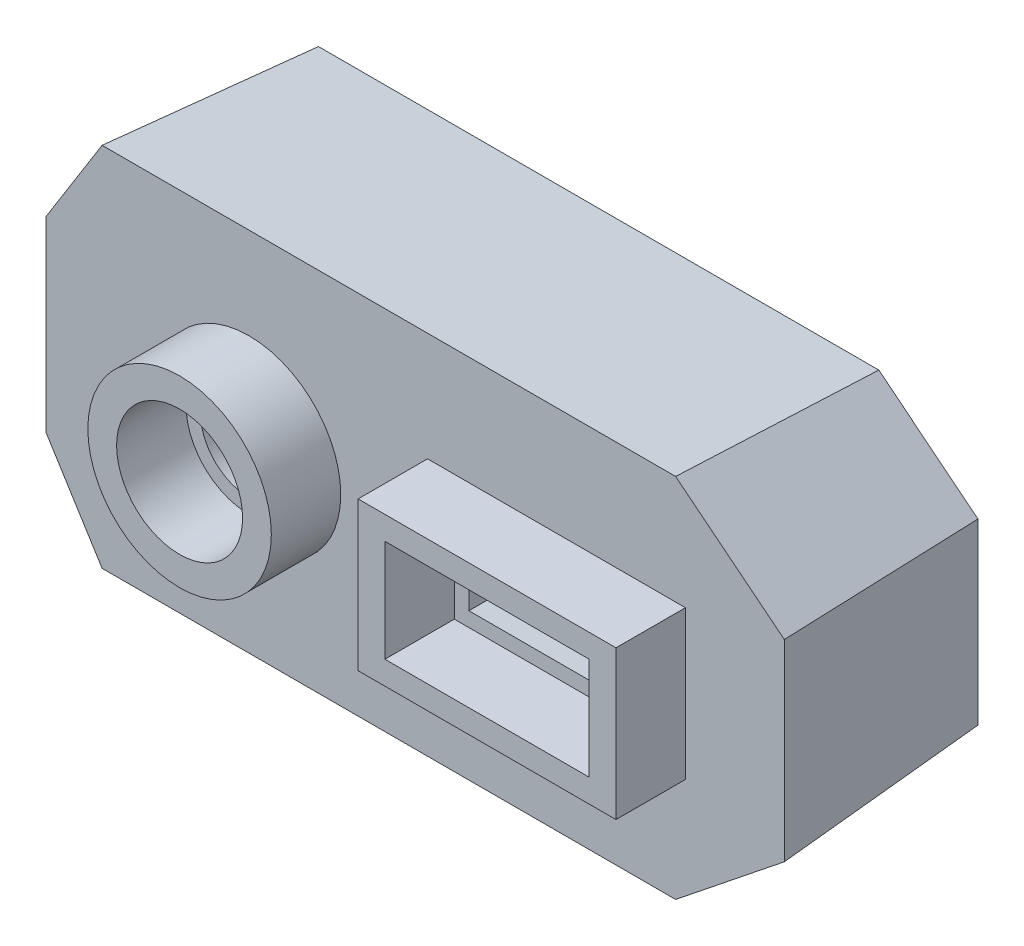
SolidWorks part; units mm, degrees
ref_plane "Front Plane" through (0, 0, 0) normal (0, 0, 1) x (1, 0, 0)
ref_plane "Top Plane" through (0, 0, 0) normal (0, 1, 0) x (1, 0, 0)
ref_plane "Right Plane" through (0, 0, 0) normal (1, 0, 0) x (0, 0, -1)
sketch "Sketch1" plane through (0, 0, 0) normal (0, 0, 1) x (1, 0, 0)
  line L0 (-28, 34) -> (85, 34)
  line L1 (85, 34) -> (105, 18)
  line L2 (105, 18) -> (105, -18)
  line L3 (105, -18) -> (85, -34)
  line L4 (85, -34) -> (-28, -34)
  line L5 (-28, -34) -> (-38, -18)
  line L6 (-38, -18) -> (-38, 18)
  line L7 (-38, 18) -> (-28, 34)
  line L9 (41.4, -10.3) -> (82.6, -10.3)
  line L10 (41.4, -10.3) -> (41.4, 10.3)
  line L11 (41.4, 10.3) -> (82.6, 10.3)
  line L12 (82.6, -10.3) -> (82.6, 10.3)
  circle A0 centre (0, 0) radius 12.7
extrude "Boss-Extrude1" add sketch "Sketch1" along normal blind 42 draft 4 draft outward yes
sketch "Sketch2" plane through (0, 0, 0) normal (0, 0, 1) x (1, 0, 0)
  line L1 (36, -15) -> (88, -15)
  line L2 (36, -15) -> (36, 15)
  line L3 (36, 15) -> (88, 15)
  line L4 (88, -15) -> (88, 15)
  line L6 (41.4, -10.3) -> (82.6, -10.3)
  line L7 (41.4, -10.3) -> (41.4, 10.3)
  line L8 (41.4, 10.3) -> (82.6, 10.3)
  line L9 (82.6, -10.3) -> (82.6, 10.3)
  circle A0 centre (0, 0) radius 18.5
  circle A1 centre (0, 0) radius 12.7
extrude "Boss-Extrude2" add sketch "Sketch2" along normal blind 56
